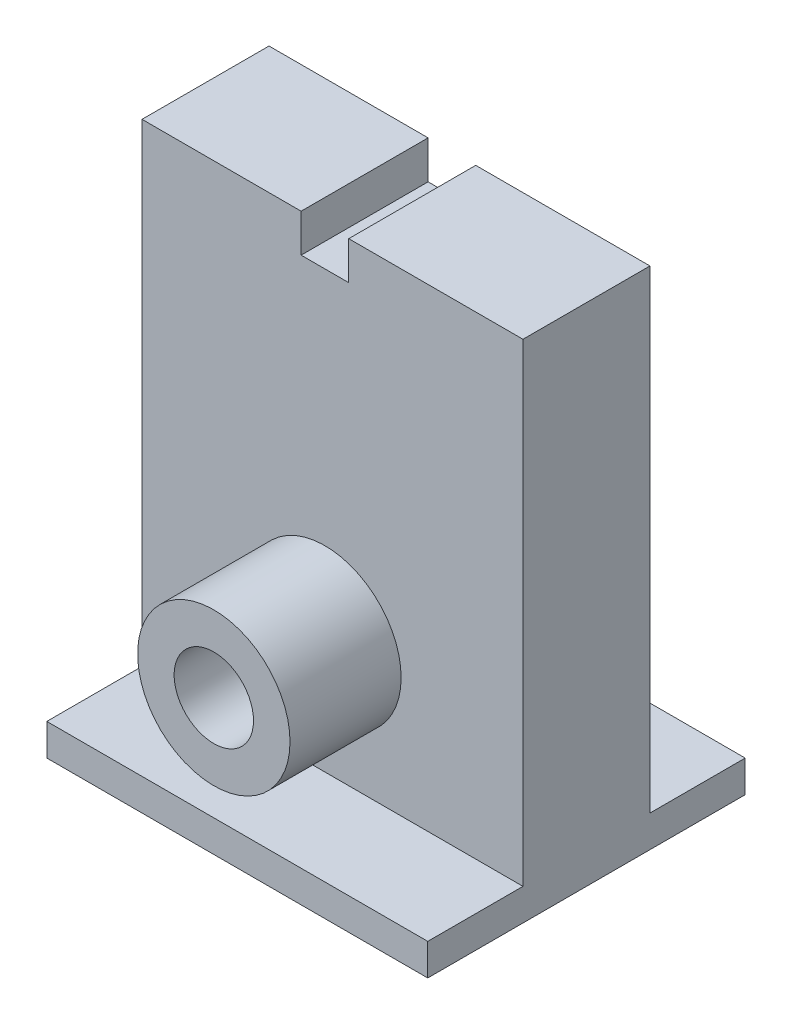
SolidWorks part; units mm, degrees
ref_plane "前视基准面" through (0, 0, 0) normal (0, 0, 1) x (1, 0, 0)
ref_plane "上视基准面" through (0, 0, 0) normal (0, 1, 0) x (1, 0, 0)
ref_plane "右视基准面" through (0, 0, 0) normal (1, 0, 0) x (0, 0, -1)
other "Configuration Table"
sketch "草图1" plane through (0, 0, 0) normal (0, 0, 1) x (1, 0, 0)
  line L0 (-57.6145, 24.0242) -> (62.3855, 24.0242)
  line L1 (62.3855, 24.0242) -> (62.3855, -123.2258)
  line L2 (62.3855, -123.2258) -> (-57.6145, -123.2258)
  line L3 (-57.6145, -123.2258) -> (-57.6145, 24.0242)
  dimension "D1" = 147.25
  dimension "D2" = 120
extrude "凸台-拉伸1" add sketch "草图1" along normal blind 40
sketch "草图2" plane through (0, 24.0242, 0) normal (0, 1, 0) x (1, 0, 0)
  line L0 (-57.6145, 0) -> (-7.5, 0)
  line L1 (62.3855, 0) -> (-57.6145, 0) construction
  line L2 (-7.5, 0) -> (-7.5, -40)
  line L3 (62.3855, -40) -> (-57.6145, -40) construction
  line L4 (-7.5, -40) -> (-57.6145, -40)
  line L5 (-57.6145, -40) -> (-57.6145, 0)
  line L6 (7.5, 0) -> (7.5, -40)
  line L7 (7.5, -40) -> (62.3855, -40)
  line L8 (62.3855, -40) -> (62.3855, 0)
  line L9 (62.3855, 0) -> (7.5, 0)
  line L10 (0, 0) -> (0, 50000) construction
  dimension "D1" = 7.5
  dimension "D2" = 7.5
extrude "凸台-拉伸2" add sketch "草图2" along normal blind 12
sketch "草图3" plane through (0, 0, 40) normal (0, 0, 1) x (1, 0, 0)
  line L0 (0, 0) -> (0, -50000) construction
  line L1 (-57.6145, -123.2258) -> (62.3855, -123.2258) construction
  circle A0 centre (0, -75.4758) radius 12.5
  circle A1 centre (0, -75.4758) radius 24
  dimension "D1" = 25
  dimension "D2" = 47.75
extrude "凸台-拉伸3" add sketch "草图3" along normal blind 35
ref_plane "基准面1" through (0, 0, 20) normal (0, 0, 1) x (1, 0, 0)
mirror "镜向1" about plane through (0, 0, 20) normal (0, 0, 1) of "凸台-拉伸3"
sketch "草图4" plane through (0, -123.2258, 0) normal (0, -1, 0) x (1, 0, 0)
  line L0 (-57.6145, -30) -> (-57.6145, 70)
  line L1 (-57.6145, 40) -> (-57.6145, 0) construction
  line L2 (-57.6145, 70) -> (62.3855, 70)
  line L3 (62.3855, 70) -> (62.3855, -30)
  line L4 (62.3855, 40) -> (62.3855, 0) construction
  line L5 (-57.6145, 20) -> (-50057.6145, 20) construction
  line L7 (-57.6145, -30) -> (62.3855, -30)
  point P11 (62.3855, 20)
  point P12 (-57.6145, 20)
  dimension "D1" = 50
extrude "凸台-拉伸4" add sketch "草图4" against normal blind 10
